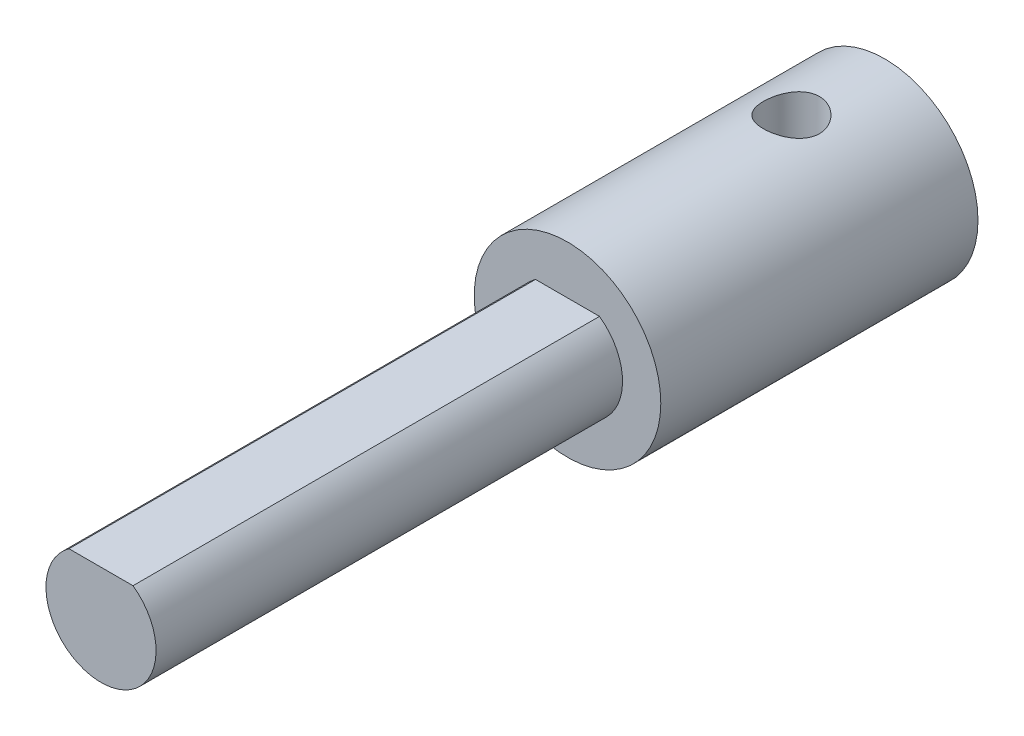
SolidWorks part; units mm, degrees
ref_plane "Front" through (0, 0, 0) normal (0, 0, 1) x (1, 0, 0)
ref_plane "Top" through (0, 0, 0) normal (0, 1, 0) x (1, 0, 0)
ref_plane "Right" through (0, 0, 0) normal (1, 0, 0) x (0, 0, -1)
sketch "Sketch1" plane through (0, 0, 0) normal (0, 0, 1) x (1, 0, 0)
  line L0 (-1.6562, 2.65) -> (1.6562, 2.65)
  line L1 (0, 0) -> (0, 2.65) construction
  line L2 (0, 2.65) -> (0, 3.125) construction
  circle A0 centre (0, 0) radius 3.125
  circle A1 centre (0, 0) radius 5
  dimension "D1" = 6.25
  dimension "D3" = 10
  dimension "D2" = 2.65
extrude "Boss-Extrude1" add sketch "Sketch1" along normal blind 15 contours A1 A0 | L0 A0
sketch "Sketch3" plane through (0, 0, 0) normal (0, 1, 0) x (1, 0, 0)
  circle A0 centre (0, -5) radius 1.5
  dimension "D1" = 3
  dimension "D2" = 5
extrude "Cut-Extrude1" cut sketch "Sketch3" along normal up to next
sketch "Sketch4" plane through (0, 0, 15) normal (0, 0, 1) x (1, 0, 0)
  circle A0 centre (0, 0) radius 5
  circle A1 centre (0, 0) radius 5 construction
extrude "Boss-Extrude2" add sketch "Sketch4" along normal blind 2
sketch "Sketch6" plane through (0, 0, 17) normal (0, 0, 1) x (1, 0, 0)
  line L0 (-1.7154, 2.4) -> (1.7154, 2.4)
  circle A0 centre (0, 0) radius 2.95
  dimension "D1" = 5.9
  dimension "D2" = 2.4
extrude "Boss-Extrude3" add sketch "Sketch6" along normal blind 25 contours L0 A0
